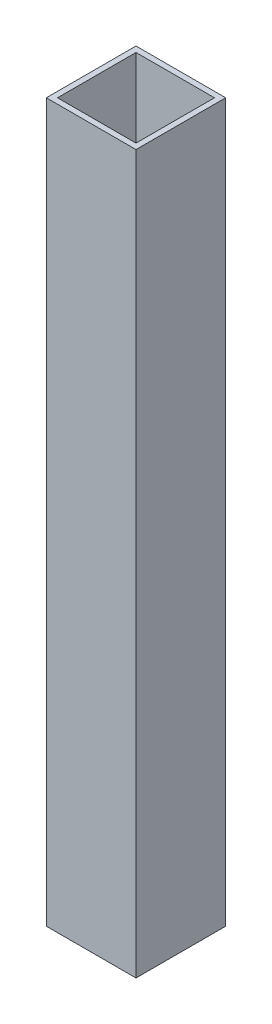
SolidWorks part; units mm, degrees
material "6061 Alloy"
ref_plane "Front Plane" through (0, 0, 0) normal (0, 0, 1) x (1, 0, 0)
ref_plane "Top Plane" through (0, 0, 0) normal (0, 1, 0) x (1, 0, 0)
ref_plane "Right Plane" through (0, 0, 0) normal (1, 0, 0) x (0, 0, -1)
sketch "Sketch1" plane through (0, 0, 0) normal (0, 1, 0) x (1, 0, 0)
  line L1 (12.7, -12.7) -> (-12.7, -12.7)
  line L2 (12.7, -12.7) -> (12.7, 12.7)
  line L3 (12.7, 12.7) -> (-12.7, 12.7)
  line L4 (-12.7, -12.7) -> (-12.7, 12.7)
  line L5 (12.7, -12.7) -> (-12.7, 12.7) construction
  line L6 (12.7, 12.7) -> (-12.7, -12.7) construction
  line L7 (11.1125, -11.1125) -> (-11.1125, -11.1125)
  line L8 (11.1125, -11.1125) -> (11.1125, 11.1125)
  line L9 (11.1125, 11.1125) -> (-11.1125, 11.1125)
  line L10 (-11.1125, -11.1125) -> (-11.1125, 11.1125)
  line L11 (11.1125, -11.1125) -> (-11.1125, 11.1125) construction
  line L12 (11.1125, 11.1125) -> (-11.1125, -11.1125) construction
  point P0 (0, 0)
  point P6 (0, 0)
  dimension "D1" = 25.4
  dimension "D2" = 25.4
  dimension "D3" = 1.5875
extrude "Boss-Extrude1" add sketch "Sketch1" along normal blind 203.2
